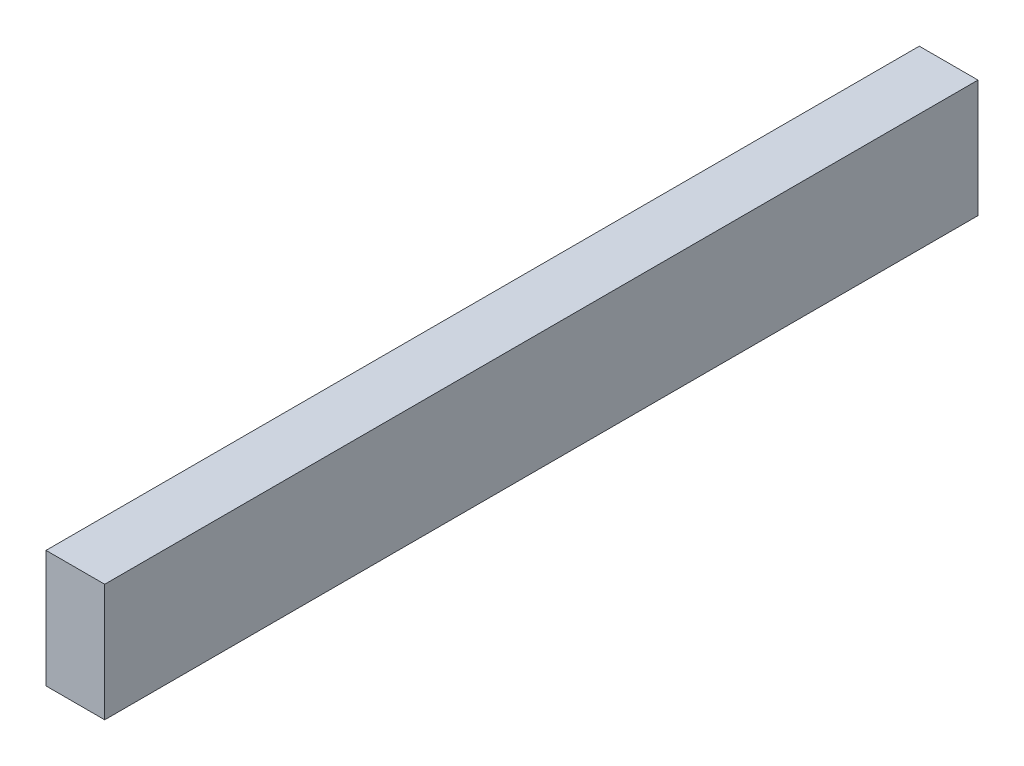
SolidWorks part; units mm, degrees
material "Balsa"
ref_plane "Front Plane" through (0, 0, 0) normal (0, 0, 1) x (1, 0, 0)
ref_plane "Top Plane" through (0, 0, 0) normal (0, 1, 0) x (1, 0, 0)
ref_plane "Right Plane" through (0, 0, 0) normal (1, 0, 0) x (0, 0, -1)
sketch "Sketch1" plane through (0, 0, 0) normal (0, 1, 0) x (1, 0, 0)
  line L1 (-25.358, -11.2463) -> (25.442, -11.2463)
  line L2 (-25.358, -11.2463) -> (-25.358, 744.4037)
  line L3 (-25.358, 744.4037) -> (25.442, 744.4037)
  line L4 (25.442, -11.2463) -> (25.442, 744.4037)
  line L5 (-25.358, -11.2463) -> (25.442, 744.4037) construction
  line L6 (-25.358, 744.4037) -> (25.442, -11.2463) construction
  point P0 (0.042, 366.5787)
  dimension "D1" = 50.8
  dimension "D2" = 755.65
extrude "Boss-Extrude1" add sketch "Sketch1" against normal blind 101.6
